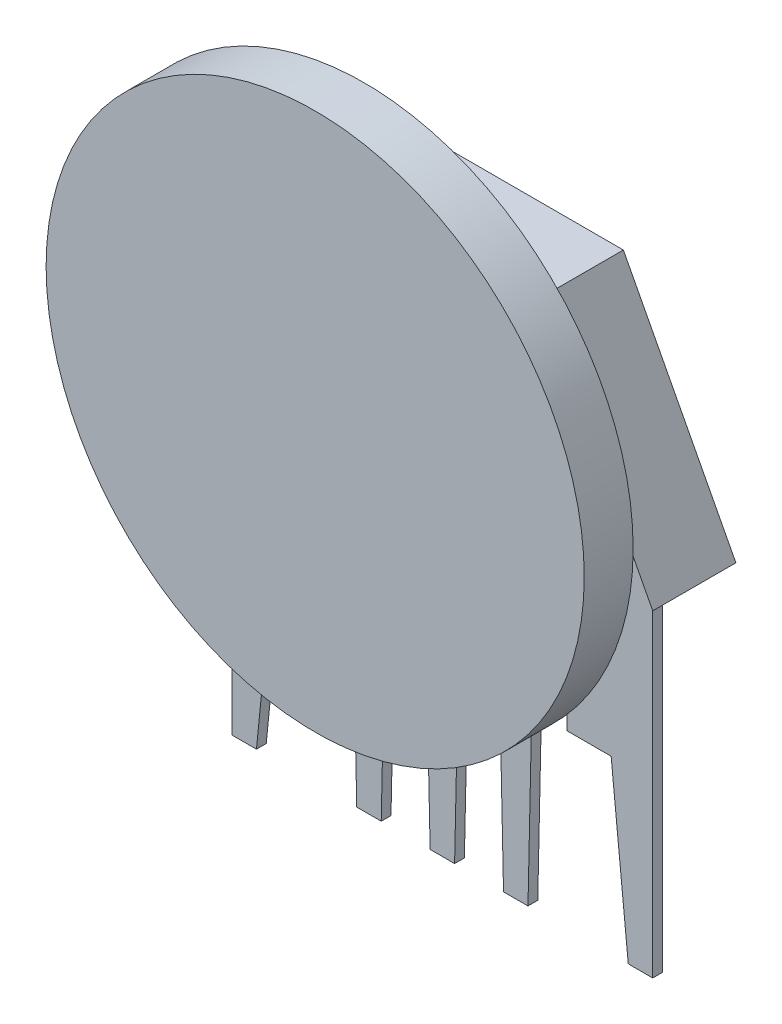
SolidWorks part; units mm, degrees
ref_plane "Front Plane" through (0, 0, 0) normal (0, 0, 1) x (1, 0, 0)
ref_plane "Top Plane" through (0, 0, 0) normal (0, 1, 0) x (1, 0, 0)
ref_plane "Right Plane" through (0, 0, 0) normal (1, 0, 0) x (0, 0, -1)
sketch "Sketch1" plane through (0, 0, 0) normal (0, 0, 1) x (1, 0, 0)
  circle A0 centre (0, 0) radius 11
  dimension "D1" = 22
extrude "Boss-Extrude1" add sketch "Sketch1" along normal blind 2
sketch "Sketch2" plane through (0, 0, 0) normal (0, 0, -1) x (-1, 0, 0)
  circle A0 centre (0, 0) radius 7
  dimension "D1" = 14
extrude "Boss-Extrude2" add sketch "Sketch2" along normal blind 2.2
sketch "Sketch3" plane through (0, 0, -2.2) normal (0, 0, -1) x (-1, 0, 0)
  circle A0 centre (0, 0) radius 5.5
  dimension "D1" = 11
extrude "Boss-Extrude3" add sketch "Sketch3" along normal blind 1
sketch "Sketch4" plane through (0, 0, -3.2) normal (0, 0, -1) x (-1, 0, 0)
  line L0 (-4, 3.7749) -> (4, 3.7749)
  line L1 (4, 3.7749) -> (8.6, -5)
  line L2 (8.6, -5) -> (8.6, -18)
  line L3 (8.6, -18) -> (7.6, -18)
  line L4 (7.6, -18) -> (6.9, -11)
  line L5 (6.9, -11) -> (5.1, -11)
  line L6 (5.1, -11) -> (5.1, -2.0591)
  line L7 (5.1, -2.0591) -> (3.85, -2.0591)
  line L8 (0, -5.5) -> (0, 3.7749) construction
  line L9 (3.85, -2.0591) -> (3.5, -18)
  line L10 (3.5, -18) -> (2.5, -18)
  line L11 (2.5, -18) -> (2.15, -2.0591)
  line L12 (2.15, -2.0591) -> (0.85, -2.0591)
  line L13 (0.85, -2.0591) -> (0.5, -18)
  line L14 (0.5, -18) -> (-0.5, -18)
  line L15 (-0.85, -2.0591) -> (-0.5, -18)
  line L16 (-2.15, -2.0591) -> (-0.85, -2.0591)
  line L17 (-2.5, -18) -> (-2.15, -2.0591)
  line L18 (-3.5, -18) -> (-2.5, -18)
  line L19 (-3.85, -2.0591) -> (-3.5, -18)
  line L20 (-5.1, -2.0591) -> (-3.85, -2.0591)
  line L21 (-5.1, -11) -> (-5.1, -2.0591)
  line L22 (-6.9, -11) -> (-5.1, -11)
  line L23 (-7.6, -18) -> (-6.9, -11)
  line L24 (-8.6, -18) -> (-7.6, -18)
  line L25 (-8.6, -5) -> (-8.6, -18)
  line L26 (-4, 3.7749) -> (-8.6, -5)
  circle A0 centre (0, 0) radius 5.5 construction
  circle A1 centre (0, 0) radius 5.5 construction
  point P21 (0, -18)
  point P34 (3.5612, -18)
  point P35 (4.2931, -8.8599)
  point P36 (2.7673, -18)
  point P37 (3.7673, -8.7687)
  point P38 (0, 0)
  point P39 (2.3489, -8.7864)
  point P40 (4, -8.7621)
  point P41 (3, -18)
  point P42 (5.1, -2.0591)
  dimension "D1" = 13
  dimension "D2" = 1
  dimension "D3" = 3.5
  dimension "D4" = 1.7
  dimension "D5" = 8
  dimension "D6" = 5
  dimension "D7" = 17.2
  dimension "D8" = 1.7
  dimension "D9" = 1.7
  dimension "D10" = 3
  dimension "D11" = 7
extrude "Boss-Extrude4" add sketch "Sketch4" along normal blind 0.4
sketch "Sketch5" plane through (0, 0, -3.6) normal (0, 0, -1) x (-1, 0, 0)
  line L0 (-8.6, -5) -> (-4, 3.7749)
  line L1 (-4, 3.7749) -> (4, 3.7749)
  line L2 (4, 3.7749) -> (-4, 3.7749) construction
  line L3 (4, 3.7749) -> (8.6, -5)
  line L4 (8.6, -5) -> (-8.6, -5)
  line L5 (5.3801, 1.1423) -> (4, 3.7749) construction
  circle A0 centre (0, 0) radius 5.5 construction
  point P4 (4, 3.7749)
extrude "Boss-Extrude5" add sketch "Sketch5" along normal blind 3
